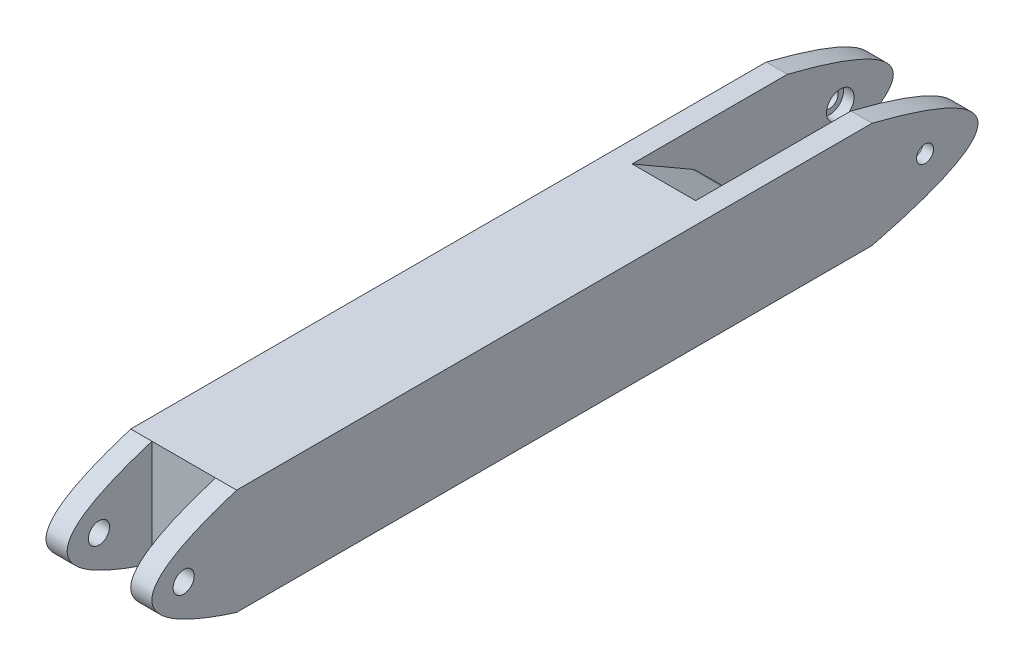
SolidWorks part; units mm, degrees
ref_plane "Front Plane" through (0, 0, 0) normal (0, 0, 1) x (1, 0, 0)
ref_plane "Top Plane" through (0, 0, 0) normal (0, 1, 0) x (1, 0, 0)
ref_plane "Right Plane" through (0, 0, 0) normal (1, 0, 0) x (0, 0, -1)
sketch "Sketch1" plane through (0, 0, 0) normal (1, 0, 0) x (0, 0, -1)
  line L0 (-255.8715, 42.046) -> (44.1285, 42.046)
  line L3 (-255.8715, -7.954) -> (44.1285, -7.954)
  circle A0 centre (-280.8715, 17.046) radius 5
  circle A1 centre (69.1285, 17.046) radius 4
  spline S0 degree 2 poles (44.1285, 42.046) (144.1285, 17.046) (44.1285, -7.954) knots 0 0 0 1 1 1
  spline S1 degree 2 poles (-255.8715, 42.046) (-335.8715, 17.046) (-255.8715, -7.954) knots 0 0 0 1 1 1
  dimension "D8" = 10
  dimension "D10" = 8
  dimension "D2" = 50
  dimension "D3" = 25
  dimension "D4" = 50
  dimension "D6" = 40
  dimension "D5" = 15
  dimension "D9" = 25
  dimension "D7" = 350
extrude "Boss-Extrude1" add sketch "Sketch1" along normal blind 50
sketch "Sketch2" plane through (0, 0, 0) normal (0, 1, 0) x (1, 0, 0)
  line L0 (50, 94.1285) -> (0, 94.1285) construction
  line L1 (10, 94.1285) -> (40, 94.1285)
  line L2 (10, 94.1285) -> (10, 14.1285)
  line L3 (10, 14.1285) -> (40, 14.1285)
  line L4 (40, 94.1285) -> (40, 14.1285)
  line L6 (0, 94.1285) -> (0, 44.1285) construction
  dimension "D1" = 10
  dimension "D2" = 10
  dimension "D3" = 80
extrude "Cut-Extrude1" cut sketch "Sketch2" along normal blind 52 and the other way blind 35
sketch "Sketch3" plane through (0, -7.954, 0) normal (0, -1, 0) x (1, 0, 0)
  line L0 (50, 295.8715) -> (0, 295.8715) construction
  line L1 (10, 295.8715) -> (40, 295.8715)
  line L2 (10, 295.8715) -> (10, 255.8715)
  line L3 (10, 255.8715) -> (40, 255.8715)
  line L4 (40, 295.8715) -> (40, 255.8715)
  line L5 (50, 255.8715) -> (0, 255.8715) construction
  dimension "D1" = 10
  dimension "D2" = 10
extrude "Cut-Extrude2" cut sketch "Sketch3" against normal blind 52
sketch "Sketch4" plane through (0, 0, 0) normal (-1, 0, 0) x (0, 0, 1)
  line L1 (-44.1285, 42.046) -> (255.8715, 42.046) construction
  line L5 (-14.1285, 17.046) -> (-14.1285, 42.046)
  line L6 (-14.1285, 42.046) -> (29.1728, 42.046)
  line L7 (-14.1285, 17.046) -> (29.1728, 42.046)
  line L8 (-14.1285, -7.954) -> (-14.1285, 42.046) construction
  dimension "D1" = 25
  dimension "D2" = 60
  dimension "D3" = 0
extrude "Cut-Extrude3" cut sketch "Sketch4" against normal blind 30 from offset 10 offset against normal yes
sketch "Sketch5" plane through (0, 0, 0) normal (-1, 0, 0) x (0, 0, 1)
  line L0 (-14.1285, -7.954) -> (-14.1285, 17.046)
  line L1 (-14.1285, 17.046) -> (29.1728, -7.954)
  line L2 (255.8715, -7.954) -> (-44.1285, -7.954) construction
  line L3 (29.1728, -7.954) -> (-14.1285, -7.954)
  line L5 (-14.1285, -7.954) -> (-14.1285, 17.046) construction
  dimension "D1" = 25
  dimension "D2" = 60
  dimension "D3" = 0
extrude "Cut-Extrude4" cut sketch "Sketch5" against normal blind 30 from offset 10 offset against normal yes
fillet "Fillet1" radius 10 1 edges at (25, 17.046, -14.1285)
sketch "Sketch6" plane through (10, 0, 0) normal (1, 0, 0) x (0, 0, -1)
  circle A0 centre (69.1285, 17.046) radius 6.5
  dimension "D1" = 13
sketch "Sketch7" plane through (40, 0, 0) normal (-1, 0, 0) x (0, 0, 1)
  circle A0 centre (-69.1285, 17.046) radius 6.5
  dimension "D1" = 13
extrude "Cut-Extrude5" cut sketch "Sketch7" against normal blind 5
extrude "Cut-Extrude6" cut sketch "Sketch6" against normal blind 5
sketch "Sketch8" plane through (0, 0, 0) normal (-1, 0, 0) x (0, 0, 1)
  line L0 (-69.1285, 17.046) -> (78.6046, 17.046) construction
  circle A1 centre (15.8715, 7.046) radius 3
  circle A2 centre (15.8715, 27.046) radius 3
  dimension "D1" = 6
  dimension "D3" = 85
  dimension "D4" = 10
extrude "Cut-Extrude8" cut sketch "Sketch8" against normal blind 16
equation "\"bearing_d_in\"=8"
equation "\"b\"=8"
equation "\"bearing_d_out\"=13"
equation "\"D1@Sketch6\"=\"bearing_d_out\""
equation "\"bearing_width\"=5"
equation "\"D1@Cut-Extrude5\"=\"bearing_width\""
equation "\"length_thigh\"=350"
equation "\"D7@Sketch1\"=\"length_thigh\""
equation "\"width_thigh\"=50"
equation "\"D2@Sketch1\"=\"width_thigh\""
equation "\"length_thigh_cut\"=80"
equation "\"D3@Sketch2\"=\"length_thigh_cut\""
